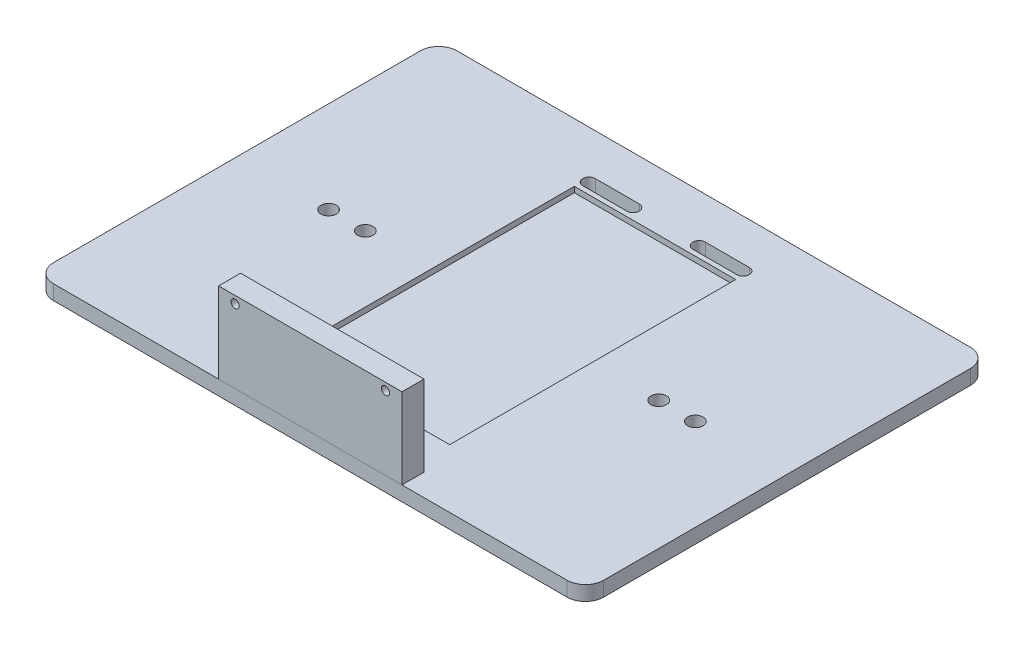
SolidWorks part; units mm, degrees
ref_plane "Front Plane" through (0, 0, 0) normal (0, 0, 1) x (1, 0, 0)
ref_plane "Top Plane" through (0, 0, 0) normal (0, 1, 0) x (1, 0, 0)
ref_plane "Right Plane" through (0, 0, 0) normal (1, 0, 0) x (0, 0, -1)
sketch "Sketch1" plane through (0, 0, 0) normal (0, 1, 0) x (1, 0, 0)
  line L0 (-75, 0) -> (75, 0) construction
  line L1 (-75, -55) -> (75, -55)
  line L2 (-75, -55) -> (-75, 55)
  line L3 (-75, 55) -> (75, 55)
  line L4 (75, -55) -> (75, 55)
  line L5 (-75, -55) -> (75, 55) construction
  line L6 (-75, 55) -> (75, -55) construction
  point P0 (0, 0)
  dimension "D1" = 150
  dimension "D2" = 110
extrude "Boss-Extrude1" add sketch "Sketch1" along normal blind 4
fillet "Fillet1" radius 5 4 edges at (-75, 2, -55) (-75, 2, 55) (75, 2, -55) (75, 2, 55)
sketch "Sketch2" plane through (0, 4, 0) normal (0, 1, 0) x (1, 0, 0)
  line L0 (-75, 0) -> (75, 0) construction
  line L1 (-75, 50) -> (-75, -50) construction
  line L2 (75, -50) -> (75, 50) construction
  line L3 (0, 55) -> (0, -55) construction
  line L4 (70, 55) -> (-70, 55) construction
  line L5 (-70, -55) -> (70, -55) construction
  circle A0 centre (-50, 0) radius 2.1
  circle A1 centre (-40, 0) radius 2.1
  dimension "D1" = 4.2
  dimension "D2" = 50
  dimension "D3" = 4.2
  dimension "D4" = 40
extrude "Cut-Extrude1" cut sketch "Sketch2" against normal through all
sketch "Sketch3" plane through (0, 0, 0) normal (0, -1, 0) x (1, 0, 0)
  line L0 (-75, 0) -> (75, 0) construction
  line L1 (-75, -50) -> (-75, 50) construction
  line L2 (75, 50) -> (75, -50) construction
  line L3 (0, 55) -> (0, -55) construction
  line L4 (-70, 55) -> (70, 55) construction
  line L5 (70, -55) -> (-70, -55) construction
  circle A0 centre (-50, 0) radius 3
  circle A1 centre (-40, 0) radius 3
  dimension "D1" = 6
  dimension "D2" = 6
extrude "Boss-Extrude2" add sketch "Sketch3" along normal blind 2
mirror "Mirror1" about plane through (0, 0, 0) normal (1, 0, 0) of "Boss-Extrude2", "Cut-Extrude1"
sketch "Sketch4" plane through (0, 4, 0) normal (0, 1, 0) x (1, 0, 0)
  line L0 (0, -55) -> (0, 55) construction
  line L1 (-22, -39) -> (-6, -39)
  line L2 (-22, -39) -> (-22, 39)
  line L3 (-22, 39) -> (22, 39)
  line L4 (22, -39) -> (22, 39)
  line L5 (-22, -39) -> (22, 39) construction
  line L6 (-22, 39) -> (22, -39) construction
  line L7 (-70, -55) -> (70, -55) construction
  line L8 (70, 55) -> (-70, 55) construction
  line L9 (6, -39) -> (22, -39)
  line L10 (-6, -43) -> (6, -43)
  line L11 (-6, -43) -> (-6, -39)
  line L13 (6, -43) -> (6, -39)
  line L14 (-6, -43) -> (6, -39) construction
  line L15 (-6, -39) -> (6, -43) construction
  point P0 (0, 0)
  point P15 (0, -41)
  dimension "D1" = 44
  dimension "D2" = 78
  dimension "D3" = 0
  dimension "D4" = 4
  dimension "D5" = 12
extrude "Cut-Extrude2" cut sketch "Sketch4" against normal blind 1.5
sketch "Sketch7" plane through (0, 0, 55) normal (0, 0, 1) x (1, 0, 0)
  line L0 (-70, 4) -> (70, 4) construction
  line L1 (-25, 4) -> (25, 4)
  line L2 (-25, 4) -> (-25, 26)
  line L3 (-25, 26) -> (25, 26)
  line L4 (25, 4) -> (25, 26)
  line L5 (-25, 4) -> (25, 26) construction
  line L6 (-25, 26) -> (25, 4) construction
  line L7 (70, 0) -> (70, 4) construction
  point P0 (0, 4)
  point P10 (0, 26)
  dimension "D1" = 50
  dimension "D2" = 22
  dimension "D3" = 45
extrude "Boss-Extrude4" add sketch "Sketch7" against normal blind 6 separate body
sketch "Sketch8" plane through (0, 0, 49) normal (0, 0, -1) x (-1, 0, 0)
  line L0 (0, 4) -> (0, 26) construction
  line L1 (25, 4) -> (-25, 4) construction
  line L2 (-25, 26) -> (25, 26) construction
  circle A0 centre (-20.5, 24) radius 1.1
  circle A1 centre (20.5, 24) radius 1.1
  dimension "D1" = 2.2
  dimension "D2" = 20.5
  dimension "D3" = 20
extrude "Cut-Extrude3" cut sketch "Sketch8" against normal through all
sketch "Sketch9" plane through (0, 0, 0) normal (0, -1, 0) x (1, 0, 0)
  line L0 (0, 55) -> (0, -55) construction
  line L1 (-70, 55) -> (70, 55) construction
  line L2 (70, -55) -> (-70, -55) construction
  line L3 (-21, -42) -> (-9, -42) construction
  line L4 (-21, -40.3) -> (-9, -40.3)
  line L5 (-21, -43.7) -> (-9, -43.7)
  line L6 (-75, 0) -> (75, 0) construction
  line L7 (-75, -50) -> (-75, 50) construction
  line L8 (75, 50) -> (75, -50) construction
  line L9 (21, -42) -> (9, -42) construction
  line L10 (21, -40.3) -> (9, -40.3)
  line L11 (21, -43.7) -> (9, -43.7)
  arc A0 (-21, -40.3) -> (-21, -43.7) centre (-21, -42) ccw
  arc A1 (-9, -43.7) -> (-9, -40.3) centre (-9, -42) ccw
  arc A2 (21, -40.3) -> (21, -43.7) centre (21, -42) cw
  arc A3 (9, -43.7) -> (9, -40.3) centre (9, -42) cw
  point P8 (-15, -42)
  point P22 (15, -42)
  dimension "D1" = 12
  dimension "D2" = 3.4
  dimension "D3" = 15
  dimension "D4" = 42
extrude "Cut-Extrude4" cut sketch "Sketch9" against normal through all
sketch "Sketch10" plane through (0, 4, 0) normal (0, 1, 0) x (1, 0, 0)
  circle A0 centre (-50, 0) radius 2.1
  circle A1 centre (-40, 0) radius 2.1
  circle A2 centre (40, 0) radius 2.1
  circle A3 centre (50, 0) radius 2.1
  dimension "D1" = 4.2
  dimension "D2" = 4.2
  dimension "D3" = 4.2
  dimension "D4" = 4.2
extrude "Cut-Extrude5" cut sketch "Sketch10" against normal through all
